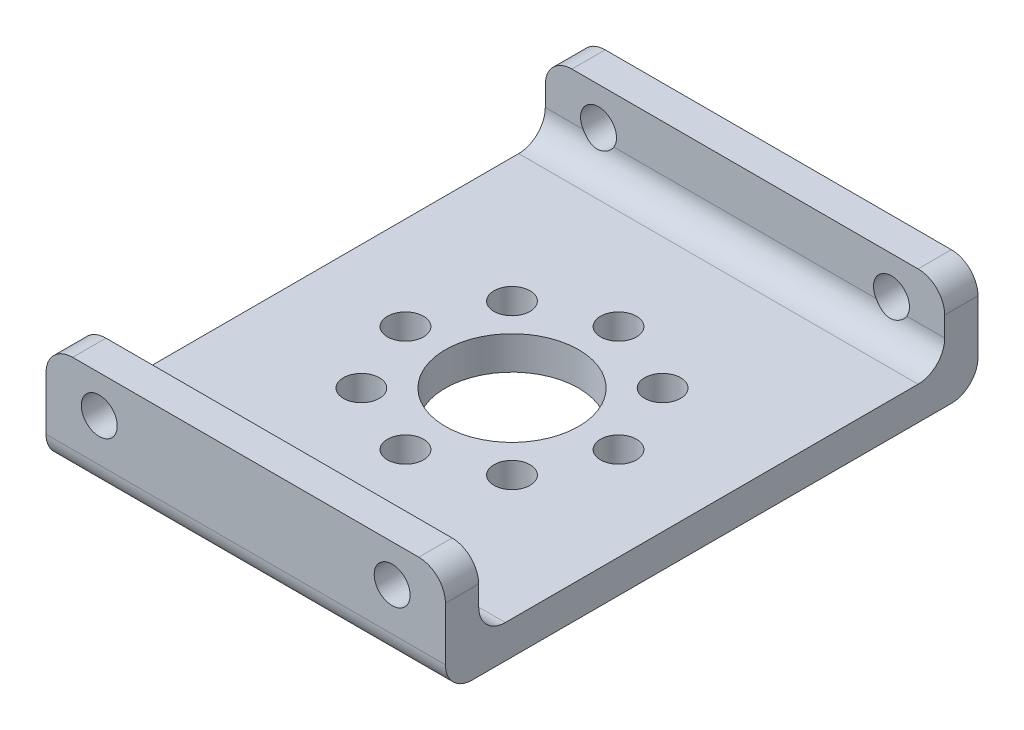
SolidWorks part; units mm, degrees
ref_plane "Plano frontal" through (0, 0, 0) normal (0, 0, 1) x (1, 0, 0)
ref_plane "Plano superior" through (0, 0, 0) normal (0, 1, 0) x (1, 0, 0)
ref_plane "Plano direito" through (0, 0, 0) normal (1, 0, 0) x (0, 0, -1)
sketch "Esboço1" plane through (0, 0, 0) normal (0, 0, 1) x (1, 0, 0)
  line L1 (-15, 15) -> (15, 15)
  line L2 (-15, 15) -> (-15, -15)
  line L3 (-15, -15) -> (15, -15)
  line L4 (15, 15) -> (15, -15)
  line L5 (-15, 15) -> (15, -15) construction
  line L6 (-15, -15) -> (15, 15) construction
  point P0 (0, 0)
  dimension "D1" = 30
  dimension "D2" = 30
extrude "Ressalto-extrusão1" add sketch "Esboço1" along normal blind 40
sketch "Esboço2" plane through (15, 0, 0) normal (1, 0, 0) x (0, 0, -1)
  line L0 (-40, 15) -> (-40, -15)
  line L1 (-40, -15) -> (0, -15)
  line L2 (0, -15) -> (0, 15)
  line L3 (-37.5, 15) -> (-37.5, -12.5)
  line L4 (-37.5, -12.5) -> (-2.5, -12.5)
  line L5 (-2.5, -12.5) -> (-2.5, 15)
  line L6 (-37.5, 15) -> (-2.5, 15)
  line M3 (0, 15) -> (-40, 15)
  dimension "D1" = 2.5
extrude "Corte-extrusão1" cut sketch "Esboço2" against normal blind 40 contours L4 L5 L3 M3
fillet "Filete1" radius 2 4 edges at (15, 15, 38.75) (-15, 15, 38.75) (-15, 15, 1.25) (15, 15, 1.25)
fillet "Filete2" radius 2 4 edges at (0, -12.5, 37.5) (0, -12.5, 2.5) (0, -15, 40) (0, -15, 0)
sketch "Esboço4" plane through (0, -15, 0) normal (0, -1, 0) x (-1, 0, 0)
  line L0 (-15, -38) -> (-15, -2) construction
  line L2 (-15, 0) -> (15, 0) construction
  circle A0 centre (0, -20) radius 5
  dimension "D1" = 10
  dimension "D2" = 15
  dimension "D3" = 20
extrude "Corte-extrusão3" cut sketch "Esboço4" against normal through all
sketch "Esboço5" plane through (0, -15, 0) normal (0, -1, 0) x (-1, 0, 0)
  line L0 (-5, -20) -> (0, -20)
  circle A0 centre (0, -20) radius 5 construction
  circle A1 centre (0, -28) radius 1.35
  circle A2 centre (-8, -20) radius 1.35
  circle A3 centre (0, -12) radius 1.35
  circle A4 centre (8, -20) radius 1.35
  circle A6 centre (-5.6569, -14.3431) radius 1.35
  circle A7 centre (5.6569, -14.3431) radius 1.35
  circle A8 centre (5.6569, -25.6569) radius 1.35
  circle A9 centre (-5.6569, -25.6569) radius 1.35
  dimension "D2" = 8
  dimension "D3" = 8
  dimension "D4" = 8
  dimension "D5" = 8
  dimension "D6" = 8
  dimension "D7" = 8
  dimension "D8" = 8
  dimension "D9" = 2.7
  dimension "D10" = 2.7
  dimension "D11" = 2.7
  dimension "D12" = 2.7
  dimension "D13" = 2.7
  dimension "D14" = 2.7
  dimension "D15" = 2.7
  dimension "D16" = 2.7
  dimension "D17" = 8
  dimension "D18" = 6.1229
  dimension "D19" = 6.1229
extrude "Corte-extrusão5" cut sketch "Esboço5" against normal through all contours A1 | A9 | A2 | A6 | A3 | A7 | A4 | A8
sketch "Esboço7" plane through (0, 0, 0) normal (0, 0, -1) x (-1, 0, 0)
  line L0 (-15, -13) -> (-15, 13) construction
  line L1 (15, 13) -> (15, -13) construction
  line L2 (-13, 15) -> (13, 15) construction
  circle A0 centre (-11, 12.2) radius 1.35
  circle A1 centre (11, 12.2) radius 1.35
  dimension "D1" = 2.7
  dimension "D2" = 2.7
  dimension "D3" = 4
  dimension "D4" = 4
  dimension "D5" = 2.8
  dimension "D6" = 2.8
extrude "Corte-extrusão6" cut sketch "Esboço7" against normal through all
sketch "Esboço8" plane through (0, 0, 0) normal (0, 0, -1) x (-1, 0, 0)
  line L0 (-15, -13) -> (15, -13) construction
  line L1 (-15, -13) -> (-15, 13) construction
  line L2 (-15, -7) -> (15, -7)
  line L3 (15, 13) -> (15, -13) construction
  line L4 (15, -7) -> (15, 15)
  line L5 (-15, -7) -> (-15, 15)
  line L6 (-15, 15) -> (15, 15)
  dimension "D1" = 6
extrude "Corte-extrusão8" cut sketch "Esboço8" against normal through all
fillet "Filete3" radius 2 4 edges at (15, -7, 1.25) (-15, -7, 1.25) (-15, -7, 38.75) (15, -7, 38.75)
sketch "Esboço10" plane through (0, 0, 0) normal (0, 0, -1) x (-1, 0, 0)
  line L0 (-15, -13) -> (-15, -9) construction
  line L1 (15, -9) -> (15, -13) construction
  line L2 (-13, -7) -> (13, -7) construction
  circle A0 centre (-11, -9.8) radius 1.35
  circle A1 centre (11, -9.8) radius 1.35
  dimension "D1" = 2.7
  dimension "D2" = 2.7
  dimension "D3" = 4
  dimension "D4" = 4
  dimension "D5" = 2.8
  dimension "D6" = 2.8
extrude "Corte-extrusão9" cut sketch "Esboço10" against normal through all
